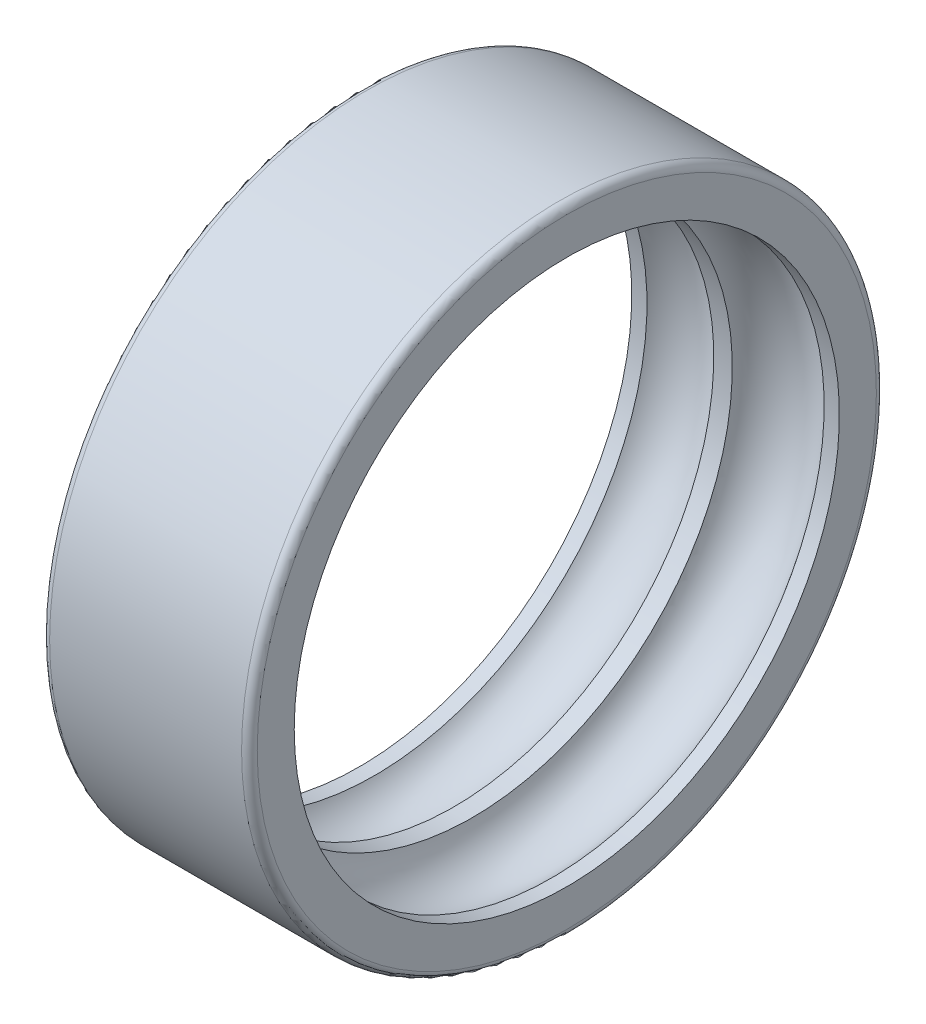
SolidWorks part; units mm, degrees
ref_plane "Piano frontale" through (0, 0, 0) normal (0, 0, 1) x (1, 0, 0)
ref_plane "Piano superiore" through (0, 0, 0) normal (0, 1, 0) x (1, 0, 0)
ref_plane "Piano destro" through (0, 0, 0) normal (1, 0, 0) x (0, 0, -1)
ref_plane "Piano1" through (0, 0, 0) normal (0, 0, 1) x (1, 0, 0)
sketch "Schizzo1" plane through (0, 0, 0) normal (0, 0, 1) x (1, 0, 0)
  line L0 (0, 82.9) -> (0, 73)
  line L1 (0, 73) -> (4.0752, 73)
  line L2 (25.3213, 69.6375) -> (30.2787, 69.6375)
  line L3 (51.5248, 73) -> (55.6, 73)
  line L4 (55.6, 73) -> (55.6, 82.9)
  line L5 (53.5, 85) -> (2.1, 85)
  line L6 (27.8, 0) -> (0, 0) construction
  arc A0 (4.0752, 73) -> (25.3213, 69.6375) centre (13.9, 66.275) cw
  arc A1 (30.2787, 69.6375) -> (51.5248, 73) centre (41.7, 66.275) cw
  arc A2 (55.6, 82.9) -> (53.5, 85) centre (53.5, 82.9) ccw
  arc A3 (2.1, 85) -> (0, 82.9) centre (2.1, 82.9) ccw
revolve "Rivoluzione1" add sketch "Schizzo1" angle 360 about L6
